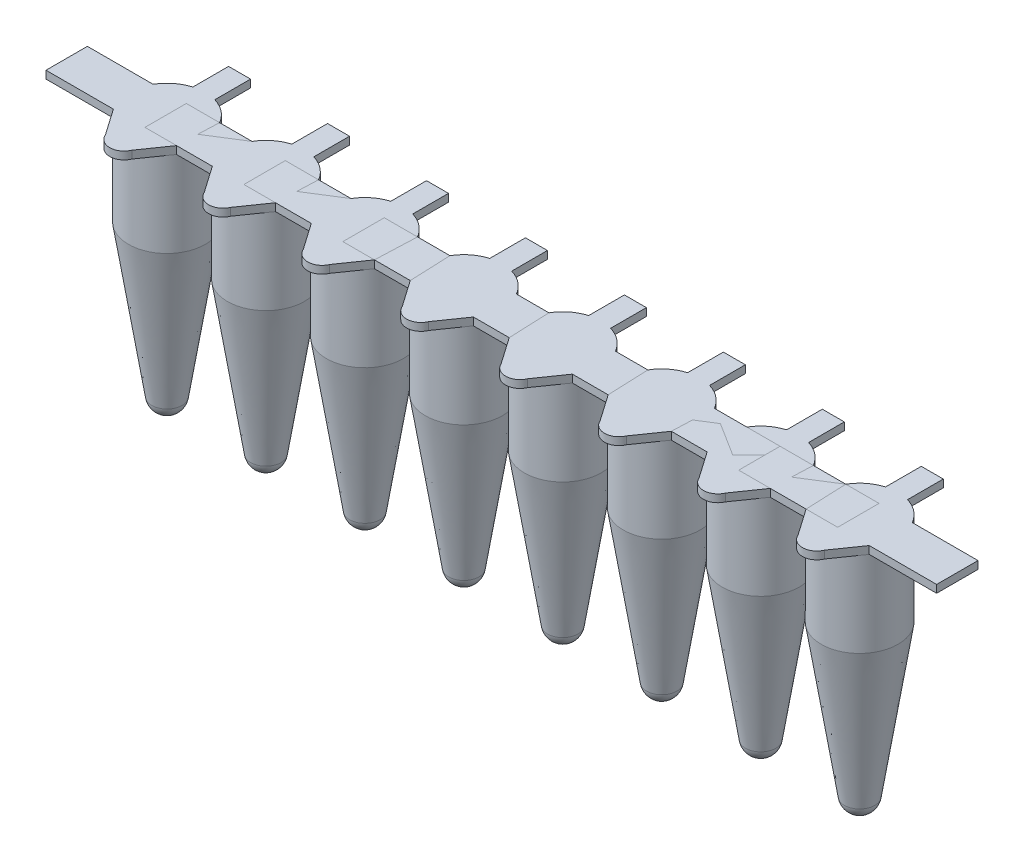
SolidWorks part; units mm, degrees
ref_plane "Front Plane" through (0, 0, 0) normal (0, 0, 1) x (1, 0, 0)
ref_plane "Top Plane" through (0, 0, 0) normal (0, 1, 0) x (1, 0, 0)
ref_plane "Right Plane" through (0, 0, 0) normal (1, 0, 0) x (0, 0, -1)
sketch "Sketch1" plane through (0, 0, 0) normal (0, 0, 1) x (1, 0, 0)
  line L0 (0, -1.4) -> (0, 31.0731) construction
  line L2 (-3.5, 22) -> (0, 22)
  line L5 (-3.5, 22) -> (-3.5, 13.5368)
  line L6 (-3.5, 13.5368) -> (-1.3837, -0.213)
  line L7 (0, 22) -> (0, -1.4)
  arc A1 (-1.3837, -0.213) -> (0, -1.4) centre (0, 0) ccw
  dimension "D4" = 1.4
  dimension "D1" = 22
  dimension "D2" = 3.5
  dimension "D5" = 8.75
revolve "Revolve1" add sketch "Sketch1" angle 360 about L0
sketch "Sketch2" plane through (0, 22, 0) normal (0, 1, 0) x (1, 0, 0)
  line L0 (0, 0) -> (0, -7.6862) construction
  line L1 (-2.8718, -2.0007) -> (-1.1995, -4.4011)
  line L2 (-1, 3.3541) -> (-1, 6.6041)
  line L3 (-1, 6.6041) -> (1, 6.6041)
  line L6 (1, 3.3541) -> (1, 6.6041)
  line L7 (2.8718, -2.0007) -> (1.1995, -4.4011)
  line L8 (0, 8.2826) -> (0, -9.7717) construction
  line L9 (-9, 1.763) -> (-3.0236, 1.763)
  line L10 (-9, 1.763) -> (-9, -2.0007)
  line L11 (-9, -2.0007) -> (-2.8718, -2.0007)
  line L12 (9, 1.763) -> (9, -2.0007)
  line L13 (3.0236, 1.763) -> (9, 1.763)
  line L14 (2.8718, -2.0007) -> (9, -2.0007)
  arc A1 (-1.1995, -4.4011) -> (1.1995, -4.4011) centre (0, -3.9) ccw
  circle A2 centre (0, 0) radius 3.5 construction
  arc A3 (-1, 3.3541) -> (-3.0236, 1.763) centre (0, 0) ccw
  arc A4 (1, 3.3541) -> (3.0236, 1.763) centre (0, 0) cw
  dimension "D2" = 1.3
  dimension "D1" = 2
  dimension "D3" = 3.9
  dimension "D4" = 3.25
  dimension "D5" = 18
extrude "Boss-Extrude1" add sketch "Sketch2" against normal blind 0.7
pattern_linear "LPattern3" count 8 spacing 9 along (1, 0, 0) of "Revolve1", "Boss-Extrude1"
